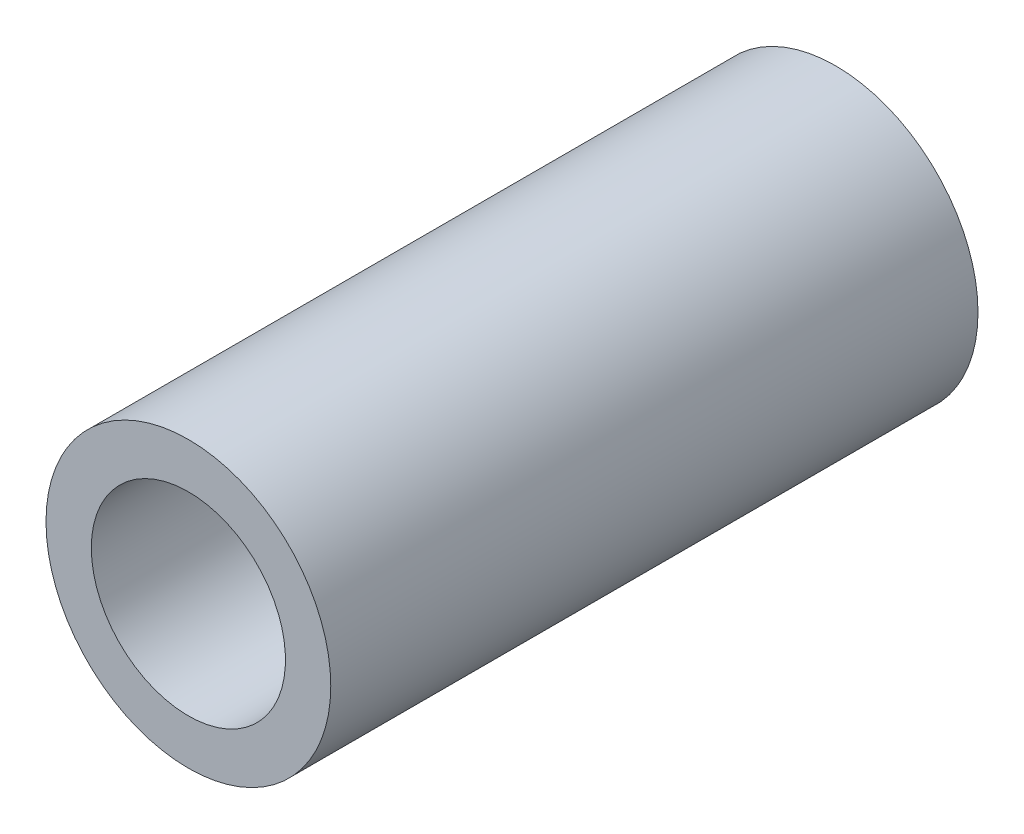
SolidWorks part; units mm, degrees
ref_plane "Plan de face" through (0, 0, 0) normal (0, 0, 1) x (1, 0, 0)
ref_plane "Plan de dessus" through (0, 0, 0) normal (0, 1, 0) x (1, 0, 0)
ref_plane "Plan de droite" through (0, 0, 0) normal (1, 0, 0) x (0, 0, -1)
sketch "Esquisse1" plane through (0, 0, 0) normal (0, 0, 1) x (1, 0, 0)
  circle A0 centre (0, 0) radius 22
extrude "Boss.-Extru.1" add sketch "Esquisse1" along normal blind 100
sketch "Esquisse2" plane through (0, 0, 0) normal (0, 0, -1) x (-1, 0, 0)
  circle A0 centre (0, 0) radius 15
extrude "Enlèv. mat.-Extru.1" cut sketch "Esquisse2" against normal blind 100
